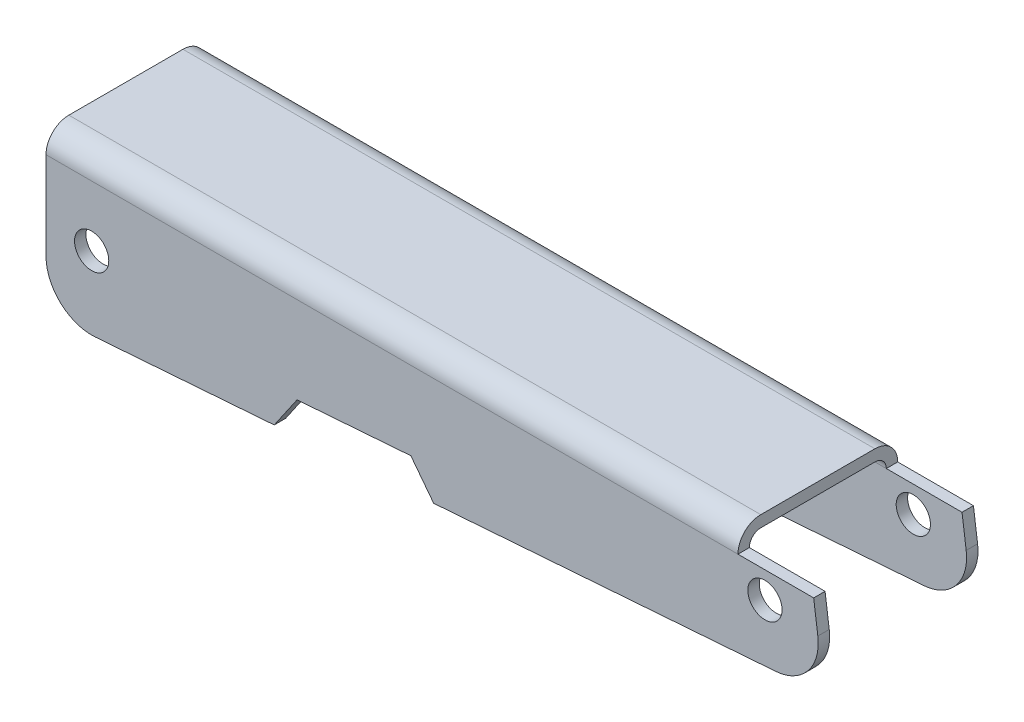
SolidWorks part; units mm, degrees
ref_plane "Front Plane" through (0, 0, 0) normal (0, 0, 1) x (1, 0, 0)
ref_plane "Top Plane" through (0, 0, 0) normal (0, 1, 0) x (1, 0, 0)
ref_plane "Right Plane" through (0, 0, 0) normal (1, 0, 0) x (0, 0, -1)
sketch "Sketch1" plane through (0, 0, 0) normal (0, 0, 1) x (1, 0, 0)
  line L0 (4, 4.3) -> (-63, 4.3)
  line L1 (-63, 4.3) -> (-63, -9.7)
  line L2 (-63, -9.7) -> (5.2, -4.6196)
  line L3 (5.2, -4.6196) -> (4, 4.3)
  circle A0 centre (0, 0) radius 1.5
  circle A1 centre (-59, -3) radius 1.5
  dimension "D3" = 3
  dimension "D7" = 7.3
  dimension "D1" = 67
  dimension "D2" = 4.3
  dimension "D4" = 9
  dimension "D5" = 4
  dimension "D6" = 1.2
  dimension "D8" = 4
  dimension "D9" = 14
extrude "Boss-Extrude1" add sketch "Sketch1" along normal mid plane 14 contours A1 | A0 | L3 L0 L1 L2
fillet "Fillet1" radius 2 2 edges at (-29.5, 4.3, -7) (-29.5, 4.3, 7)
fillet "Fillet2" radius 4 2 edges at (-63, -9.7, 0) (5.2, -4.6196, 0)
shell "Shell1" thickness 1
sketch "Sketch2" plane through (0, 0, 0) normal (0, 0, 1) x (1, 0, 0)
  line L0 (-43, -8.2102) -> (-41, -5.3036)
  line L1 (-58.7029, -9.3799) -> (0.9669, -4.935) construction
  line L2 (-41, -5.3036) -> (-31.0276, -4.5607)
  line L3 (-31.0276, -4.5607) -> (-29.0276, -7.1693)
  line L4 (-63, 2.3) -> (-63, -5.3909) construction
  line L5 (-43, -8.2102) -> (-29.0276, -7.1693)
  dimension "D1" = 2.75
  dimension "D2" = 20
  dimension "D3" = 2
  dimension "D4" = 2
  dimension "D5" = 10
extrude "Cut-Extrude1" cut sketch "Sketch2" against normal through all both and the other way through all
sketch "Sketch3" plane through (0, 4.3, 0) normal (0, 1, 0) x (1, 0, 0)
  line L0 (4.2691, -7) -> (-63, -7) construction
  line L1 (-2.366, -7) -> (4.634, -7)
  line L2 (-2.366, -7) -> (-2.366, 7)
  line L3 (-2.366, 7) -> (4.634, 7)
  line L4 (4.634, -7) -> (4.634, 7)
  dimension "D1" = 7
extrude "Cut-Extrude2" cut sketch "Sketch3" against normal up to vertex (2 mm away) up to point (4.2691, 2.3, 7)
